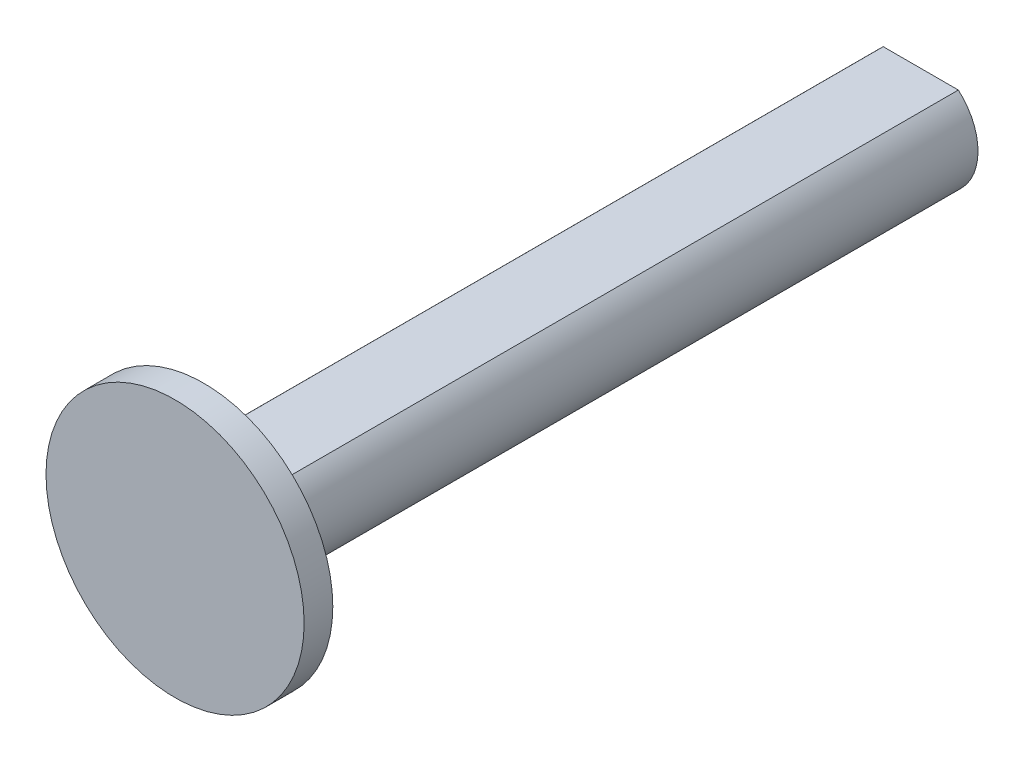
SolidWorks part; units mm, degrees
ref_plane "Front Plane" through (0, 0, 0) normal (0, 0, 1) x (1, 0, 0)
ref_plane "Top Plane" through (0, 0, 0) normal (0, 1, 0) x (1, 0, 0)
ref_plane "Right Plane" through (0, 0, 0) normal (1, 0, 0) x (0, 0, -1)
sketch "Sketch1" plane through (0, 0, 0) normal (0, 0, 1) x (1, 0, 0)
  line L0 (-2.6192, 3.01) -> (2.6192, 3.01)
  arc A0 (-2.6192, 3.01) -> (2.6192, 3.01) centre (0, 0) ccw
  arc A1 (2.6192, 3.01) -> (-2.6192, 3.01) centre (0, 0) ccw construction
  point P5 (0, -3.99)
  dimension "D1" = 7.98
  dimension "D2" = 7
extrude "Boss-Extrude1" add sketch "Sketch1" along normal mid plane 52
sketch "Esquisse1" plane through (0, 0, 26) normal (0, 0, 1) x (1, 0, 0)
  circle A0 centre (0, 0) radius 9
extrude "Boss.-Extru.1" add sketch "Esquisse1" against normal blind 2
